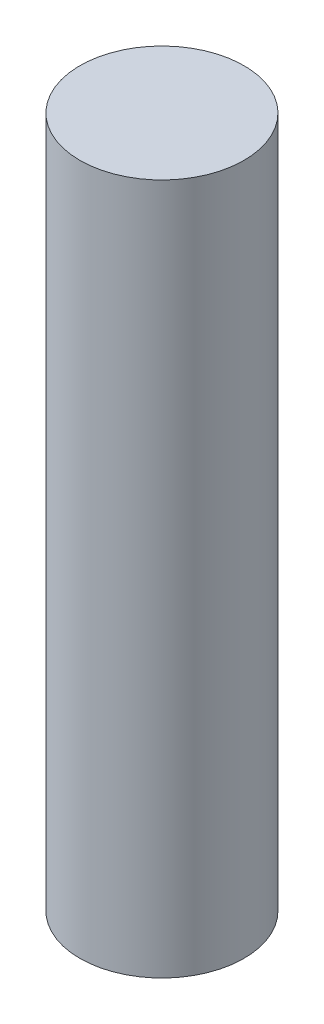
SolidWorks part; units mm, degrees
ref_plane "前视基准面" through (0, 0, 0) normal (0, 0, 1) x (1, 0, 0)
ref_plane "上视基准面" through (0, 0, 0) normal (0, 1, 0) x (1, 0, 0)
ref_plane "右视基准面" through (0, 0, 0) normal (1, 0, 0) x (0, 0, -1)
sketch "草图1" plane through (0, 0, 0) normal (0, 1, 0) x (1, 0, 0)
  circle A0 centre (-40.4789, 21.8426) radius 4.5
extrude "凸台-拉伸1" add sketch "草图1" along normal blind 37.9
